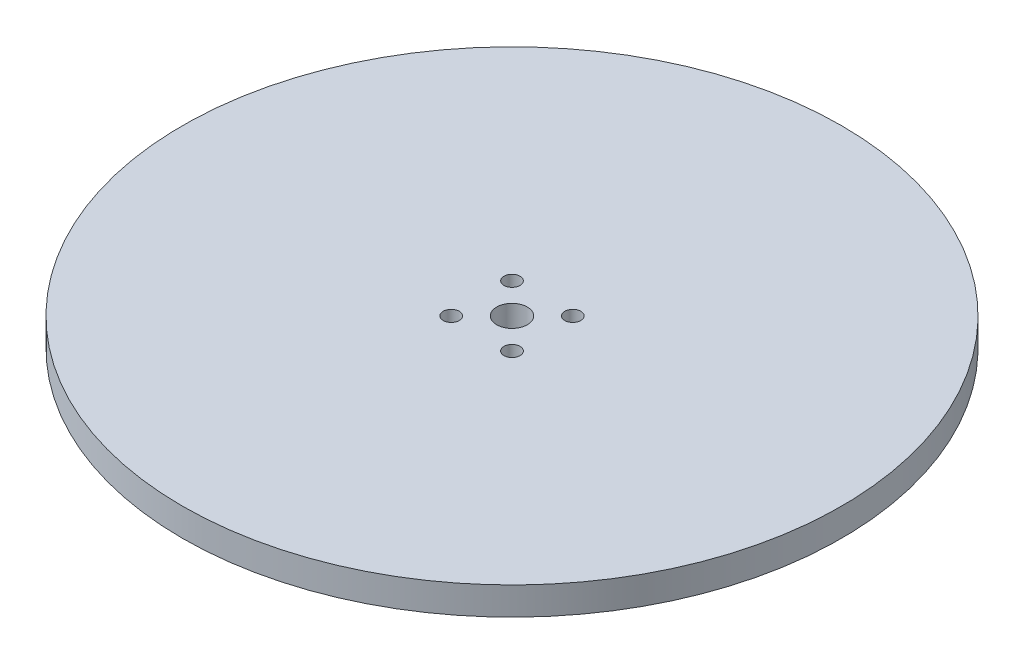
SolidWorks part; units mm, degrees
material "ABS"
ref_plane "Plan de face" through (0, 0, 0) normal (0, 0, 1) x (1, 0, 0)
ref_plane "Plan de dessus" through (0, 0, 0) normal (0, 1, 0) x (1, 0, 0)
ref_plane "Plan de droite" through (0, 0, 0) normal (1, 0, 0) x (0, 0, -1)
sketch "Esquisse1" plane through (0, 0, 0) normal (0, 1, 0) x (1, 0, 0)
  circle A0 centre (0, 0) radius 75
extrude "Boss.-Extru.1" add sketch "Esquisse1" along normal blind 6.35
sketch "Esquisse2" plane through (0, 6.35, 0) normal (0, 1, 0) x (1, 0, 0)
  circle A0 centre (0, 0) radius 3.5
  dimension "D1" = 7
extrude "Enlèv. mat.-Extru.1" cut sketch "Esquisse2" against normal up to surface (6.35 mm away) up to face at (0, 0, 75)
sketch "Sketch1" plane through (0, 0, 0) normal (0, -1, 0) x (1, 0, 0)
  circle A0 centre (-6.9148, 6.9148) radius 1.8288
  arc A2 (-6.9148, 8.6674) -> (-8.016, 5.5514) centre (-6.9148, 6.9148) ccw construction
  dimension "D1" = 3.6576
  dimension "D2" = 0
extrude "Cut-Extrude1" cut sketch "Sketch1" against normal up to surface (6.35 mm away) up to face at (0, 6.35, 3.5)
pattern_circular "CirPattern1" count 4 every 90 about axis through (0, 0, 0) along (0, 1, 0) of "Cut-Extrude1"
